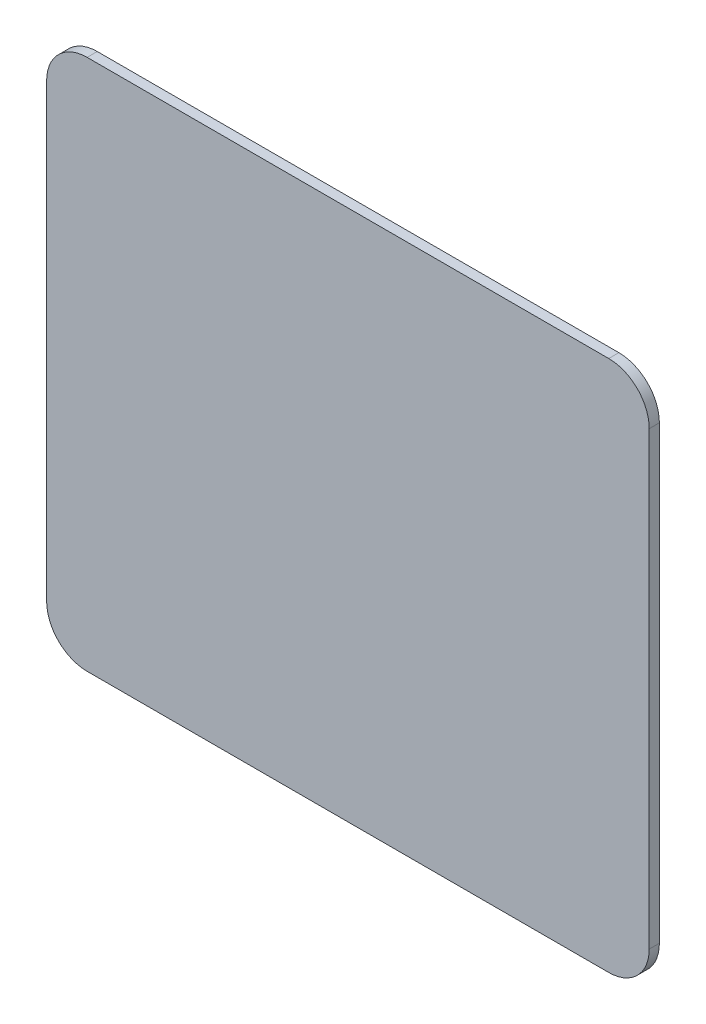
SolidWorks part; units mm, degrees
material "Acrylic (Medium-high impact)"
ref_plane "Front Plane" through (0, 0, 0) normal (0, 0, 1) x (1, 0, 0)
ref_plane "Top Plane" through (0, 0, 0) normal (0, 1, 0) x (1, 0, 0)
ref_plane "Right Plane" through (0, 0, 0) normal (1, 0, 0) x (0, 0, -1)
sketch "Sketch1" plane through (0, 0, 0) normal (0, 0, 1) x (1, 0, 0)
  line L1 (0, 0) -> (377.952, 0)
  line L2 (0, 0) -> (0, -333.502)
  line L3 (0, -333.502) -> (377.952, -333.502)
  line L4 (377.952, 0) -> (377.952, -333.502)
  dimension "D1" = 333.502
  dimension "D2" = 377.952
extrude "Boss-Extrude1" add sketch "Sketch1" along normal blind 6.35
fillet "Fillet1" radius 25.4 1 edges at (377.952, 0, 3.175)
fillet "Fillet2" radius 25.4 1 edges at (377.952, -333.502, 3.175)
fillet "Fillet3" radius 25.4 1 edges at (0, -333.502, 3.175)
fillet "Fillet4" radius 25.4 1 edges at (0, 0, 3.175)
